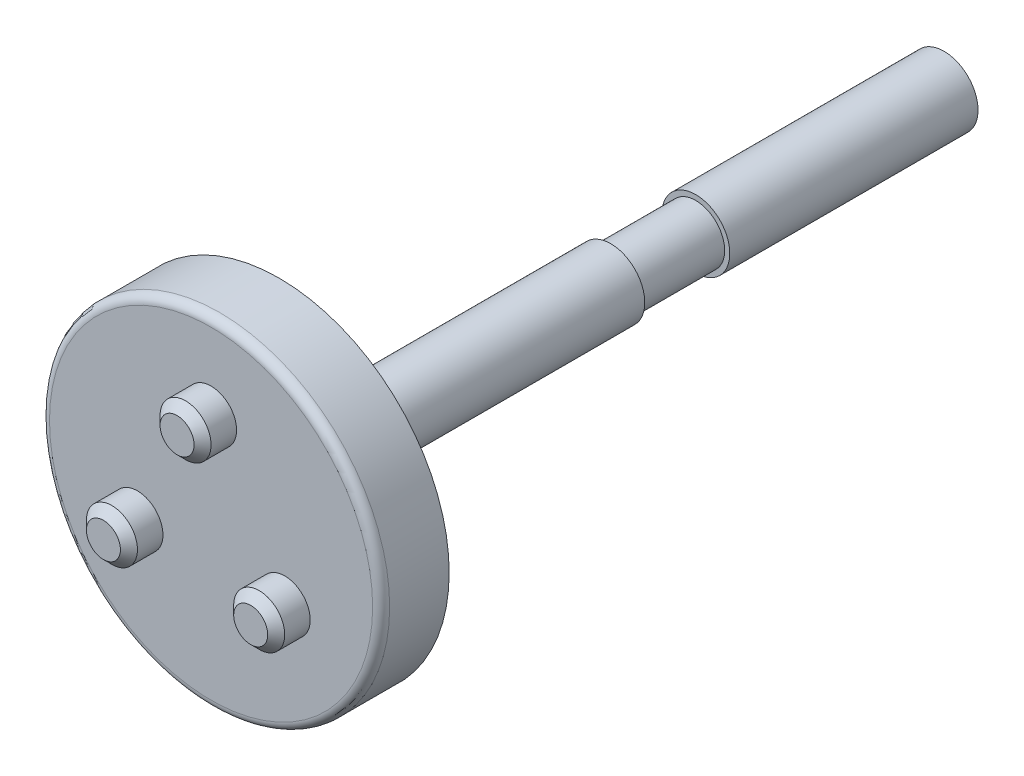
SolidWorks part; units mm, degrees
ref_plane "Front Plane" through (0, 0, 0) normal (0, 0, 1) x (1, 0, 0)
ref_plane "Top Plane" through (0, 0, 0) normal (0, 1, 0) x (1, 0, 0)
ref_plane "Right Plane" through (0, 0, 0) normal (1, 0, 0) x (0, 0, -1)
sketch "Sketch1" plane through (0, 0, 0) normal (0, 0, 1) x (1, 0, 0)
  circle A0 centre (0, 0) radius 100
  dimension "D1" = 200
extrude "Boss-Extrude1" add sketch "Sketch1" along normal blind 40
sketch "Sketch2" plane through (0, 0, 40) normal (0, 0, 1) x (1, 0, 0)
  line L0 (-100, 0) -> (100, 0) construction
  line L1 (0, 100) -> (0, -100) construction
  line L2 (0, 0) -> (0, 50) construction
  circle A0 centre (0, 0) radius 100 construction
  circle A1 centre (0, 50) radius 15
  circle A2 centre (0, 0) radius 50 construction
  circle A3 centre (43.3013, -25) radius 15
  circle A4 centre (-43.3013, -25) radius 15
  point P6 (0, 0)
  point P11 (0, 0)
  dimension "D1" = 30
  dimension "D3" = 3
  dimension "D2" = 50
  dimension "D4" = 50
extrude "Boss-Extrude2" add sketch "Sketch2" along normal blind 20
sketch "Sketch3" plane through (0, 0, 0) normal (0, 0, -1) x (-1, 0, 0)
  circle A0 centre (0, 0) radius 20
  dimension "D1" = 40
extrude "Boss-Extrude3" add sketch "Sketch3" along normal blind 495
sketch "Sketch4" plane through (0, 0, -495) normal (0, 0, -1) x (-1, 0, 0)
  circle A0 centre (0, 0) radius 17
  circle A1 centre (0, 0) radius 20 construction
  dimension "D1" = 3
extrude "Cut-Extrude1" cut sketch "Sketch4" against normal blind 50 from offset 250 flip side to cut offset against normal yes
chamfer "Chamfer1" distance 5 angle 45 3 edges at (-28.3013, -25, 60) (58.3013, -25, 60) (15, 50, 60)
fillet "Fillet1" radius 5 1 edges at (100, 0, 40)
sketch "Sketch5" plane through (0, 0, -495) normal (0, 0, -1) x (-1, 0, 0)
  circle A0 centre (0, 0) radius 20
  circle A1 centre (0, 0) radius 20 construction
  point P3 (0, 0)
extrude "Cut-Extrude2" cut sketch "Sketch5" against normal blind 104.02
